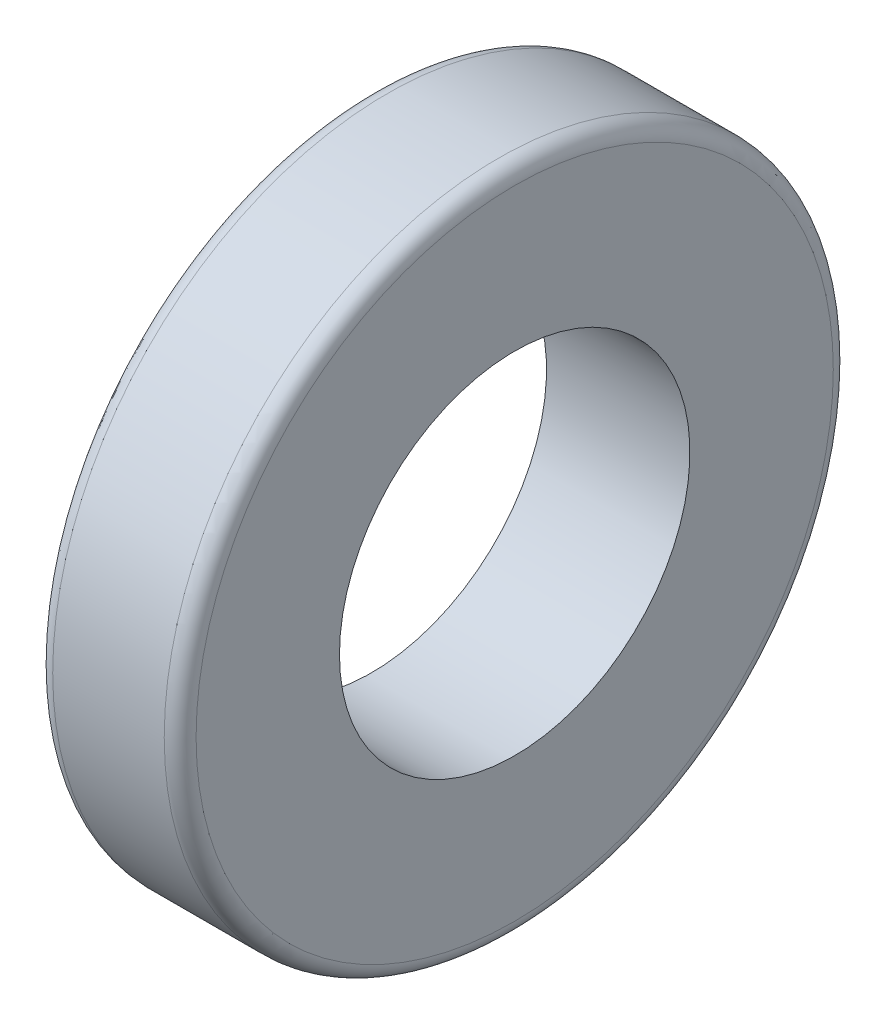
SolidWorks part; units mm, degrees
ref_plane "Front Plane" through (0, 0, 0) normal (0, 0, 1) x (1, 0, 0)
ref_plane "Top Plane" through (0, 0, 0) normal (0, 1, 0) x (1, 0, 0)
ref_plane "Right Plane" through (0, 0, 0) normal (1, 0, 0) x (0, 0, -1)
sketch "Sketch1" plane through (0, 0, 0) normal (0, 0, 1) x (1, 0, 0)
  line L0 (0, 0) -> (6, 0) construction
  line L2 (0.75, 10.5) -> (5.25, 10.5)
  line L3 (0.75, 10.5) -> (0.75, 5.5)
  line L4 (0.75, 5.5) -> (5.25, 5.5)
  line L5 (5.25, 10.5) -> (5.25, 5.5)
  line L6 (0.75, 10.5) -> (5.25, 5.5) construction
  line L7 (0.75, 5.5) -> (5.25, 10.5) construction
  point P3 (3, 8)
  point P10 (3, 0)
  dimension "D1" = 10.5
  dimension "D2" = 4.5
  dimension "D3" = 5
  dimension "D4" = 6
revolve "Revolve1" add sketch "Sketch1" angle 360 about L0
fillet "Fillet1" radius 0.5 2 edges at (0.75, 0, 10.5) (5.25, 0, 10.5)
